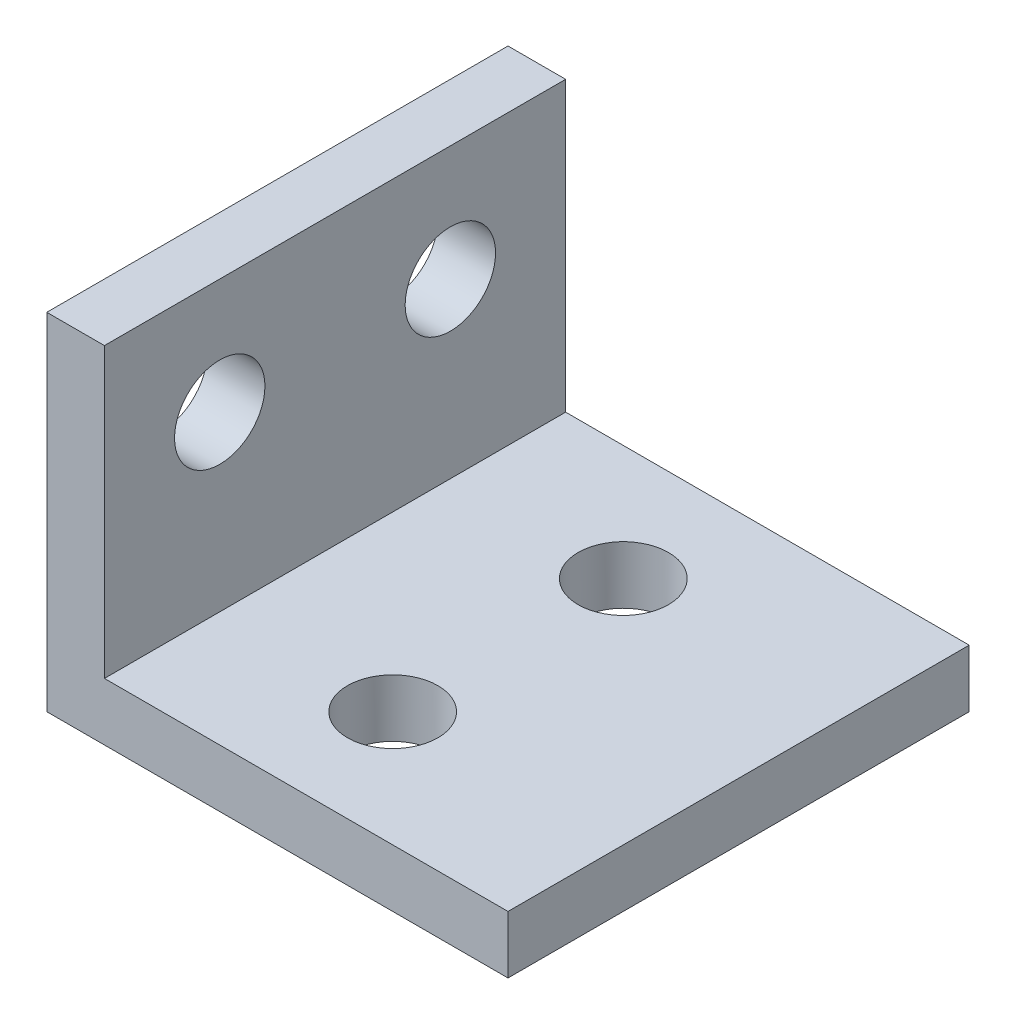
SolidWorks part; units mm, degrees
ref_plane "Front Plane" through (0, 0, 0) normal (0, 0, 1) x (1, 0, 0)
ref_plane "Top Plane" through (0, 0, 0) normal (0, 1, 0) x (1, 0, 0)
ref_plane "Right Plane" through (0, 0, 0) normal (1, 0, 0) x (0, 0, -1)
sketch "Sketch1" plane through (0, 0, 0) normal (0, 0, 1) x (1, 0, 0)
  line L0 (0, 0) -> (0, 19.05)
  line L1 (0, 19.05) -> (3.175, 19.05)
  line L2 (3.175, 19.05) -> (3.175, 3.175)
  line L3 (3.175, 3.175) -> (25.4, 3.175)
  line L4 (25.4, 3.175) -> (25.4, 0)
  line L5 (25.4, 0) -> (0, 0)
  dimension "D1" = 3.175
  dimension "D2" = 19.05
  dimension "D3" = 25.4
extrude "Boss-Extrude1" add sketch "Sketch1" along normal mid plane 25.4
sketch "Sketch3" plane through (0, 3.175, 0) normal (0, 1, 0) x (1, 0, 0)
  line L0 (0, -12.7) -> (25.4, -12.7) construction
  line L2 (25.4, -12.7) -> (3.175, -12.7) construction
  circle A0 centre (12.7, -6.35) radius 2.4892
  circle A1 centre (12.7, 6.35) radius 2.4892
  point P4 (12.7, -12.7)
  point P5 (0, 0)
  dimension "D1" = 4.9784
  dimension "D3" = 6.35
  dimension "D2" = 12.7
extrude "Cut-Extrude1" cut sketch "Sketch3" against normal through all both and the other way through all
sketch "Sketch4" plane through (3.175, 0, 0) normal (1, 0, 0) x (0, 0, -1)
  line L0 (12.7, 3.175) -> (12.7, 19.05) construction
  line L2 (-12.7, 19.05) -> (12.7, 19.05) construction
  circle A0 centre (-6.35, 12.7) radius 2.4892
  circle A1 centre (6.35, 12.7) radius 2.4892
  dimension "D1" = 4.9784
  dimension "D2" = 6.35
  dimension "D3" = 12.7
  dimension "D4" = 6.35
extrude "Cut-Extrude2" cut sketch "Sketch4" against normal through all both and the other way through all
